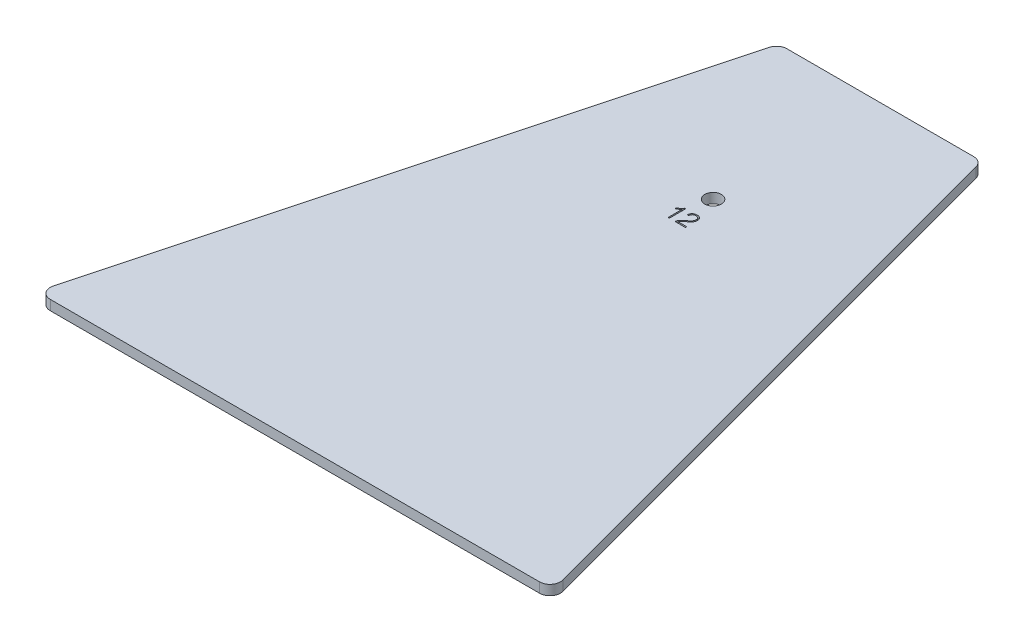
SolidWorks part; units mm, degrees
material "Acrylic (Medium-high impact)"
ref_plane "Front Plane" through (0, 0, 0) normal (0, 0, 1) x (1, 0, 0)
ref_plane "Top Plane" through (0, 0, 0) normal (0, 1, 0) x (1, 0, 0)
ref_plane "Right Plane" through (0, 0, 0) normal (1, 0, 0) x (0, 0, -1)
sketch "Sketch1" plane through (0, 0, 0) normal (0, 1, 0) x (1, 0, 0)
  line L0 (1.27, 0) -> (1.27, -355.6) construction
  line L1 (-60.325, 0) -> (62.865, 0)
  line L2 (62.865, 0) -> (158.1477, -355.6)
  line L3 (158.1477, -355.6) -> (-155.6077, -355.6)
  line L4 (-60.325, 0) -> (-155.6077, -355.6)
  dimension "D1" = 355.6
  dimension "D2" = 30
  dimension "D3" = 123.19
extrude "Boss-Extrude1" add sketch "Sketch1" along normal blind 5.9944
sketch "Sketch2" plane through (0, 5.9944, 0) normal (0, 1, 0) x (1, 0, 0)
  line L0 (1.27, 0) -> (1.27, -101.6) construction
  line L1 (62.865, 0) -> (-60.325, 0) construction
  circle A0 centre (1.27, -101.6) radius 5.08
  dimension "D1" = 10.16
  dimension "D2" = 101.6
extrude "Cut-Extrude1" cut sketch "Sketch2" against normal through all
sketch "Sketch3" plane through (0, 5.9944, 0) normal (0, 1, 0) x (1, 0, 0)
  line L0 (1.27, -101.6) -> (1.27, -114.3) construction
  line L1 (-6.985, -124.8781) -> (9.525, -124.8781) construction
  line L2 (-6.985, -124.8781) -> (-6.985, -114.3) construction
  line L3 (-6.985, -114.3) -> (9.525, -114.3) construction
  line L4 (9.525, -124.8781) -> (9.525, -114.3) construction
  text T0 "12"
  dimension "D1" = 10.5781
  dimension "D2" = 16.51
  dimension "D3" = 12.7
extrude "Cut-Extrude2" cut sketch "Sketch3" against normal blind 1.27
fillet "Fillet1" radius 6.35 4 edges at (158.1477, 2.9972, 355.6) (-155.6077, 2.9972, 355.6) (-60.325, 2.9972, 0) (62.865, 2.9972, 0)
